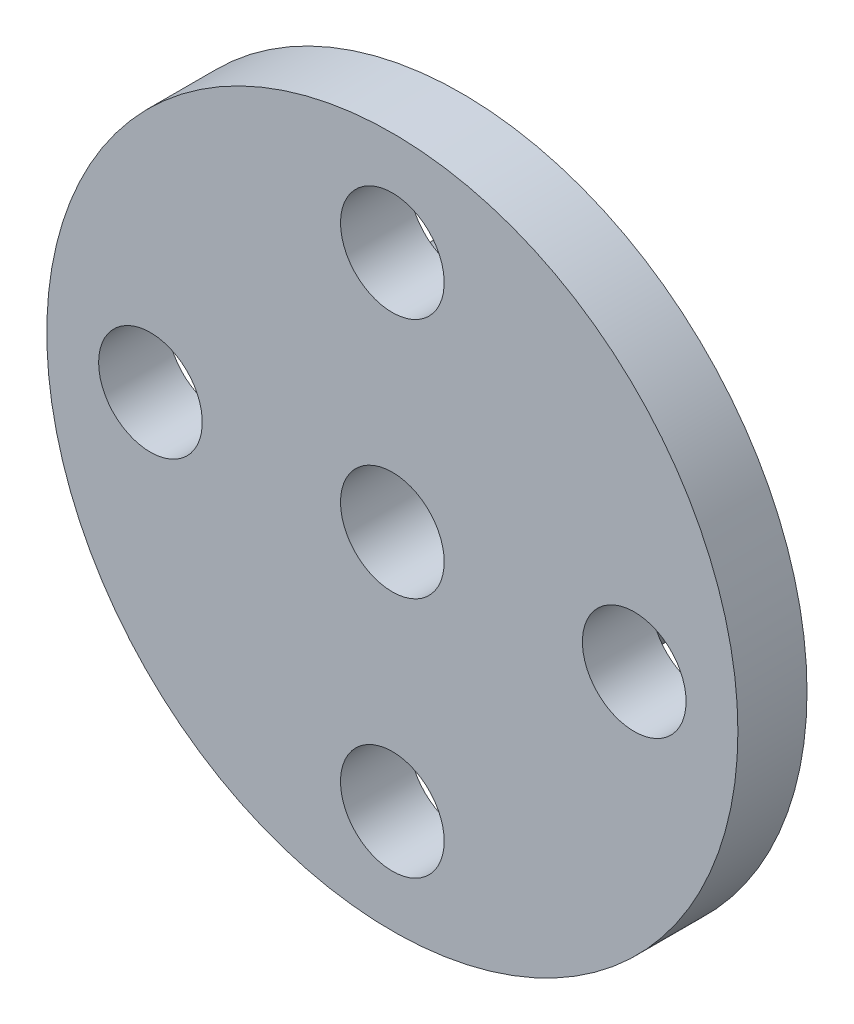
SolidWorks part; units mm, degrees
ref_plane "Plan de face" through (0, 0, 0) normal (0, 0, 1) x (1, 0, 0)
ref_plane "Plan de dessus" through (0, 0, 0) normal (0, 1, 0) x (1, 0, 0)
ref_plane "Plan de droite" through (0, 0, 0) normal (1, 0, 0) x (0, 0, -1)
sketch "Esquisse1" plane through (0, 0, 0) normal (0, 0, 1) x (1, 0, 0)
  line L0 (0, 0) -> (10, 0) construction
  line L1 (0, 11.5762) -> (0, -10.9476) construction
  line L2 (0, 0) -> (7.0711, 7.0711) construction
  circle A0 centre (0, 0) radius 10
  circle A1 centre (0, 0) radius 7 construction
  circle A2 centre (7, 0) radius 1.5
  circle A3 centre (0, 7) radius 1.5
  circle A4 centre (0, 0) radius 1.5
  circle A5 centre (0, -7) radius 1.5
  circle A6 centre (-7, 0) radius 1.5
  dimension "D2" = 20
  dimension "D3" = 45
  dimension "D1" = 3
  dimension "D4" = 14
  dimension "D5" = 3
extrude "Boss.-Extru.1" add sketch "Esquisse1" along normal blind 2
sketch "Esquisse2" plane through (0, 0, 0) normal (0, 0, -1) x (-1, 0, 0)
  circle A0 centre (0, 0) radius 1.5
  circle A1 centre (0, 0) radius 4.75
  circle A2 centre (0, 0) radius 1.5 construction
  dimension "D1" = 9.5
extrude "Boss.-Extru.2" add sketch "Esquisse2" along normal blind 3.5
